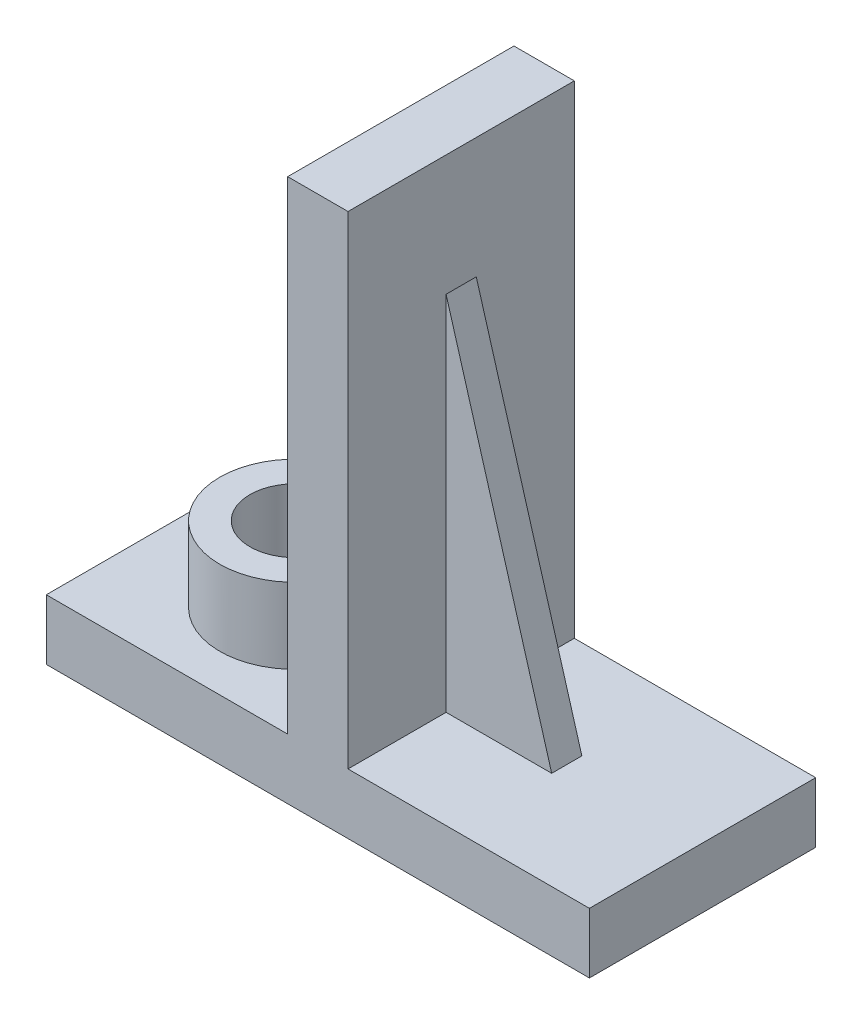
SolidWorks part; units mm, degrees
ref_plane "Front Plane" through (0, 0, 0) normal (0, 0, 1) x (1, 0, 0)
ref_plane "Top Plane" through (0, 0, 0) normal (0, 1, 0) x (1, 0, 0)
ref_plane "Right Plane" through (0, 0, 0) normal (1, 0, 0) x (0, 0, -1)
sketch "Sketch1" plane through (0, 0, 0) normal (0, 0, 1) x (1, 0, 0)
  line L1 (0, 0) -> (72, 0)
  line L2 (0, 0) -> (0, 72)
  line L3 (0, 72) -> (72, 72)
  line L4 (72, 0) -> (72, 72)
  dimension "D1" = 72
  dimension "D2" = 72
extrude "Boss-Extrude1" add sketch "Sketch1" along normal mid plane 30
sketch "Sketch4" plane through (0, 0, 15) normal (0, 0, 1) x (1, 0, 0)
  line L1 (72, 72) -> (0, 72) construction
  line L3 (40, 72) -> (72, 72)
  line L4 (72, 72) -> (72, 8)
  line L5 (72, 0) -> (72, 72) construction
  line L6 (72, 8) -> (40, 8)
  line L7 (40, 8) -> (40, 72)
  line L8 (0, 72) -> (32, 72)
  line L9 (32, 72) -> (32, 8)
  line L10 (32, 8) -> (0, 8)
  line L11 (0, 72) -> (0, 0) construction
  line L12 (0, 8) -> (0, 72)
  point P16 (0, 0)
  dimension "D1" = 8
  dimension "D2" = 32
  dimension "D3" = 8
extrude "Cut-Extrude1" cut sketch "Sketch4" against normal blind 30
sketch "Sketch8" plane through (0, 8, 0) normal (0, 1, 0) x (1, 0, 0)
  line L1 (32, 15) -> (32, -15) construction
  circle A0 centre (18, 0) radius 6
  circle A1 centre (18, 0) radius 10
  dimension "D1" = 12
  dimension "D2" = 20
  dimension "D3" = 14
extrude "Boss-Extrude2" add sketch "Sketch8" along normal blind 10
sketch "Sketch10" plane through (0, 0, 0) normal (0, 0, 1) x (1, 0, 0)
  line L0 (40, 56) -> (54, 8)
  line L1 (40, 72) -> (40, 8) construction
  line L2 (40, 8) -> (72, 8) construction
  line L11 (72, 8) -> (40, 8)
  line L12 (40, 8) -> (40, 72)
  line L13 (40, 72) -> (32, 72)
  line L14 (32, 72) -> (32, 8)
  line L15 (32, 8) -> (0, 8)
  line L16 (0, 8) -> (0, 0)
  line L17 (0, 0) -> (72, 0)
  line L18 (72, 0) -> (72, 8)
  line L19 (72, 8) -> (54, 8)
  line L20 (40, 56) -> (40, 72)
  line L21 (40, 72) -> (32, 72)
  line L22 (32, 72) -> (32, 8)
  line L23 (32, 8) -> (0, 8)
  line L24 (0, 8) -> (0, 0)
  line L25 (0, 0) -> (72, 0)
  line L26 (72, 0) -> (72, 8)
  point P6 (0, 0)
  dimension "D1" = 14
  dimension "D2" = 48
  dimension "D3" = 0
extrude "Boss-Extrude3" add sketch "Sketch10" against normal mid plane 4
